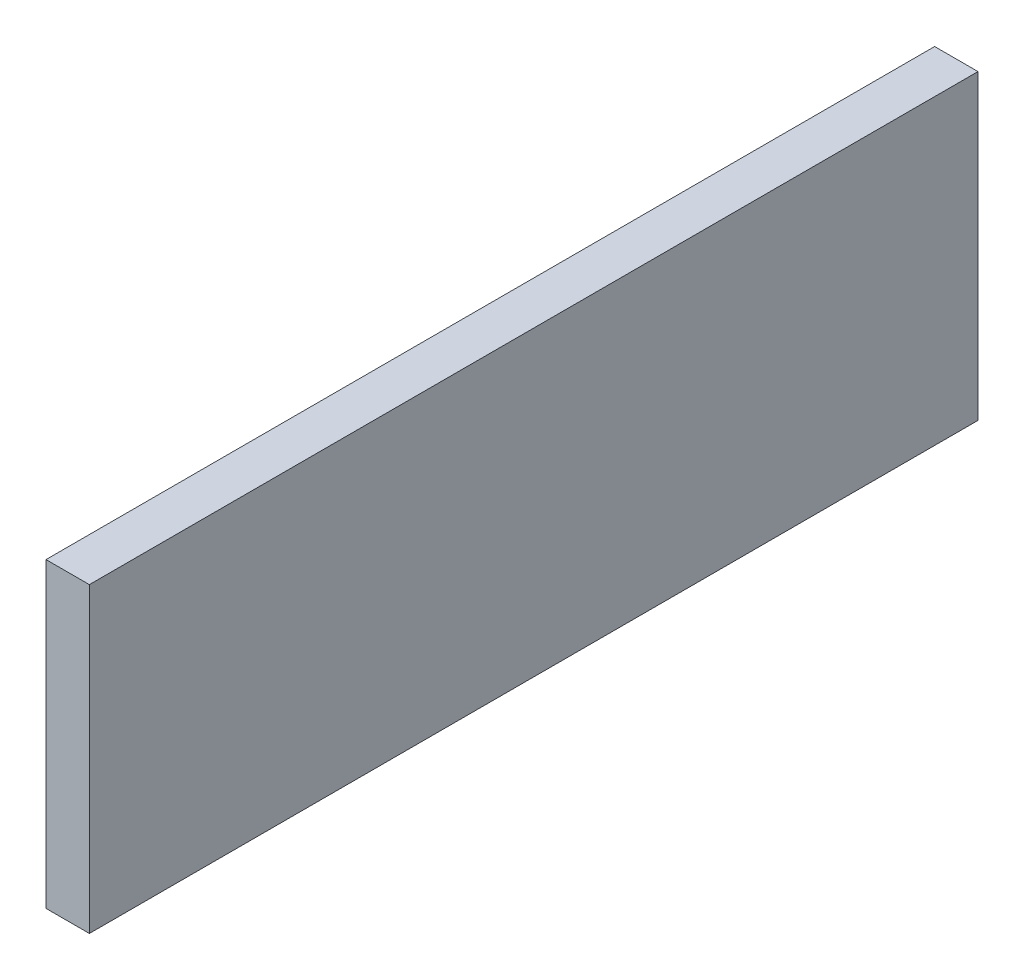
SolidWorks part; units mm, degrees
ref_plane "Front Plane" through (0, 0, 0) normal (0, 0, 1) x (1, 0, 0)
ref_plane "Top Plane" through (0, 0, 0) normal (0, 1, 0) x (1, 0, 0)
ref_plane "Right Plane" through (0, 0, 0) normal (1, 0, 0) x (0, 0, -1)
sketch "Sketch1" plane through (0, 0, 0) normal (1, 0, 0) x (0, 0, -1)
  line L1 (-125, 42.5) -> (125, 42.5)
  line L2 (-125, 42.5) -> (-125, -42.5)
  line L3 (-125, -42.5) -> (125, -42.5)
  line L4 (125, 42.5) -> (125, -42.5)
  line L5 (-125, 42.5) -> (125, -42.5) construction
  line L6 (-125, -42.5) -> (125, 42.5) construction
  point P1 (0, 0)
  dimension "D1" = 85
  dimension "D2" = 250
extrude "Boss-Extrude1" add sketch "Sketch1" along normal blind 12.2
